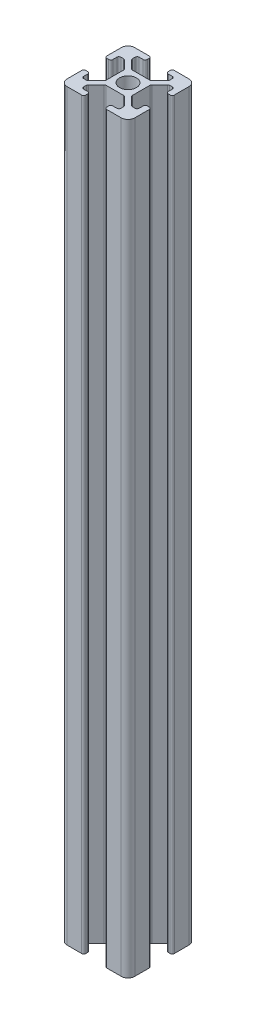
SolidWorks part; units mm, degrees
ref_plane "前视基准面" through (0, 0, 0) normal (0, 0, 1) x (1, 0, 0)
ref_plane "上视基准面" through (0, 0, 0) normal (0, 1, 0) x (1, 0, 0)
ref_plane "右视基准面" through (0, 0, 0) normal (1, 0, 0) x (0, 0, -1)
sketch "草图1" plane through (0, 0, 0) normal (0, 1, 0) x (1, 0, 0)
  line L0 (3.1, 8.8) -> (3.1, 9.4)
  line L1 (-10, -10) -> (10, -10) construction
  line L2 (-10, -10) -> (-10, 10) construction
  line L3 (-10, 10) -> (10, 10) construction
  line L4 (10, -10) -> (10, 10) construction
  line L5 (-10, -10) -> (10, 10) construction
  line L6 (-10, 10) -> (10, -10) construction
  line L7 (3.7, 10) -> (8, 10)
  line L8 (0, 10) -> (0, -10) construction
  line L9 (3.7, 8.2) -> (4.9, 8.2)
  line L10 (5.3243, 6.3849) -> (3.0151, 4.0757)
  line L11 (2.5908, 3.9) -> (0, 3.9)
  line L12 (5.5, 7.6) -> (5.5, 6.8092)
  line L13 (10, 3.7) -> (10, 8)
  line L14 (8.8, 3.1) -> (9.4, 3.1)
  line L15 (8.2, 3.7) -> (8.2, 4.9)
  line L16 (7.6, 5.5) -> (6.8092, 5.5)
  line L17 (6.3849, 5.3243) -> (4.0757, 3.0151)
  line L18 (3.9, 2.5908) -> (3.9, 0)
  line L19 (3.9, -2.5908) -> (3.9, 0)
  line L20 (2.5908, -3.9) -> (0, -3.9)
  line L21 (5.3243, -6.3849) -> (3.0151, -4.0757)
  line L22 (6.3849, -5.3243) -> (4.0757, -3.0151)
  line L23 (5.5, -7.6) -> (5.5, -6.8092)
  line L24 (3.7, -8.2) -> (4.9, -8.2)
  line L25 (3.1, -8.8) -> (3.1, -9.4)
  line L26 (3.7, -10) -> (8, -10)
  line L27 (10, -3.7) -> (10, -8)
  line L28 (8.8, -3.1) -> (9.4, -3.1)
  line L29 (8.2, -3.7) -> (8.2, -4.9)
  line L30 (7.6, -5.5) -> (6.8092, -5.5)
  line L31 (-2.5908, -3.9) -> (0, -3.9)
  line L32 (-3.9, -2.5908) -> (-3.9, 0)
  line L33 (-6.3849, -5.3243) -> (-4.0757, -3.0151)
  line L34 (-5.3243, -6.3849) -> (-3.0151, -4.0757)
  line L35 (-7.6, -5.5) -> (-6.8092, -5.5)
  line L36 (-8.2, -3.7) -> (-8.2, -4.9)
  line L37 (-8.8, -3.1) -> (-9.4, -3.1)
  line L38 (-10, -3.7) -> (-10, -8)
  line L39 (-3.7, -10) -> (-8, -10)
  line L40 (-3.1, -8.8) -> (-3.1, -9.4)
  line L41 (-3.7, -8.2) -> (-4.9, -8.2)
  line L42 (-5.5, -7.6) -> (-5.5, -6.8092)
  line L43 (-3.9, 2.5908) -> (-3.9, 0)
  line L44 (-2.5908, 3.9) -> (0, 3.9)
  line L45 (-5.3243, 6.3849) -> (-3.0151, 4.0757)
  line L46 (-6.3849, 5.3243) -> (-4.0757, 3.0151)
  line L47 (-5.5, 7.6) -> (-5.5, 6.8092)
  line L48 (-3.7, 8.2) -> (-4.9, 8.2)
  line L49 (-3.1, 8.8) -> (-3.1, 9.4)
  line L50 (-3.7, 10) -> (-8, 10)
  line L51 (-10, 3.7) -> (-10, 8)
  line L52 (-8.8, 3.1) -> (-9.4, 3.1)
  line L53 (-8.2, 3.7) -> (-8.2, 4.9)
  line L54 (-7.6, 5.5) -> (-6.8092, 5.5)
  circle A0 centre (0, 0) radius 2.5
  arc A1 (3.0151, 4.0757) -> (2.5908, 3.9) centre (2.5908, 4.5) cw
  arc A2 (5.5, 6.8092) -> (5.3243, 6.3849) centre (4.9, 6.8092) cw
  arc A3 (5.5, 7.6) -> (4.9, 8.2) centre (4.9, 7.6) ccw
  arc A4 (3.1, 8.8) -> (3.7, 8.2) centre (3.7, 8.8) ccw
  arc A5 (3.7, 10) -> (3.1, 9.4) centre (3.7, 9.4) ccw
  arc A6 (10, 3.7) -> (9.4, 3.1) centre (9.4, 3.7) cw
  arc A7 (8.8, 3.1) -> (8.2, 3.7) centre (8.8, 3.7) cw
  arc A8 (7.6, 5.5) -> (8.2, 4.9) centre (7.6, 4.9) cw
  arc A9 (6.8092, 5.5) -> (6.3849, 5.3243) centre (6.8092, 4.9) ccw
  arc A10 (4.0757, 3.0151) -> (3.9, 2.5908) centre (4.5, 2.5908) ccw
  arc A11 (10, 8) -> (8, 10) centre (8, 8) ccw
  arc A12 (3.0151, -4.0757) -> (2.5908, -3.9) centre (2.5908, -4.5) ccw
  arc A13 (4.0757, -3.0151) -> (3.9, -2.5908) centre (4.5, -2.5908) cw
  arc A14 (5.5, -6.8092) -> (5.3243, -6.3849) centre (4.9, -6.8092) ccw
  arc A15 (6.8092, -5.5) -> (6.3849, -5.3243) centre (6.8092, -4.9) cw
  arc A16 (5.5, -7.6) -> (4.9, -8.2) centre (4.9, -7.6) cw
  arc A17 (3.1, -8.8) -> (3.7, -8.2) centre (3.7, -8.8) cw
  arc A18 (3.7, -10) -> (3.1, -9.4) centre (3.7, -9.4) cw
  arc A19 (8, -10) -> (10, -8) centre (8, -8) ccw
  arc A20 (10, -3.7) -> (9.4, -3.1) centre (9.4, -3.7) ccw
  arc A21 (8.8, -3.1) -> (8.2, -3.7) centre (8.8, -3.7) ccw
  arc A22 (7.6, -5.5) -> (8.2, -4.9) centre (7.6, -4.9) ccw
  arc A23 (-4.0757, -3.0151) -> (-3.9, -2.5908) centre (-4.5, -2.5908) ccw
  arc A24 (-3.0151, -4.0757) -> (-2.5908, -3.9) centre (-2.5908, -4.5) cw
  arc A25 (-6.8092, -5.5) -> (-6.3849, -5.3243) centre (-6.8092, -4.9) ccw
  arc A26 (-5.5, -6.8092) -> (-5.3243, -6.3849) centre (-4.9, -6.8092) cw
  arc A27 (-7.6, -5.5) -> (-8.2, -4.9) centre (-7.6, -4.9) cw
  arc A28 (-8.8, -3.1) -> (-8.2, -3.7) centre (-8.8, -3.7) cw
  arc A29 (-10, -3.7) -> (-9.4, -3.1) centre (-9.4, -3.7) cw
  arc A30 (-10, -8) -> (-8, -10) centre (-8, -8) ccw
  arc A31 (-3.7, -10) -> (-3.1, -9.4) centre (-3.7, -9.4) ccw
  arc A32 (-3.1, -8.8) -> (-3.7, -8.2) centre (-3.7, -8.8) ccw
  arc A33 (-5.5, -7.6) -> (-4.9, -8.2) centre (-4.9, -7.6) ccw
  arc A34 (-3.0151, 4.0757) -> (-2.5908, 3.9) centre (-2.5908, 4.5) ccw
  arc A35 (-4.0757, 3.0151) -> (-3.9, 2.5908) centre (-4.5, 2.5908) cw
  arc A36 (-5.5, 6.8092) -> (-5.3243, 6.3849) centre (-4.9, 6.8092) ccw
  arc A37 (-6.8092, 5.5) -> (-6.3849, 5.3243) centre (-6.8092, 4.9) cw
  arc A38 (-5.5, 7.6) -> (-4.9, 8.2) centre (-4.9, 7.6) cw
  arc A39 (-3.1, 8.8) -> (-3.7, 8.2) centre (-3.7, 8.8) cw
  arc A40 (-3.7, 10) -> (-3.1, 9.4) centre (-3.7, 9.4) cw
  arc A41 (-8, 10) -> (-10, 8) centre (-8, 8) ccw
  arc A42 (-10, 3.7) -> (-9.4, 3.1) centre (-9.4, 3.7) ccw
  arc A43 (-8.8, 3.1) -> (-8.2, 3.7) centre (-8.8, 3.7) ccw
  arc A44 (-7.6, 5.5) -> (-8.2, 4.9) centre (-7.6, 4.9) ccw
  point P0 (0, 0)
  point P20 (5.5, 6.5607)
  point P25 (3.1, 8.2)
  point P28 (3.1, 10)
  point P156 (0, 0)
  dimension "D3" = 5
  dimension "D9" = 0.6
  dimension "D10" = 2
  dimension "D1" = 20
  dimension "D2" = 20
  dimension "D4" = 6.1
  dimension "D5" = 1.5
  dimension "D6" = 1.8
  dimension "D7" = 3.1
  dimension "D8" = 4.5
  dimension "D11" = 4
extrude "凸台-拉伸1" add sketch "草图1" along normal blind 220
